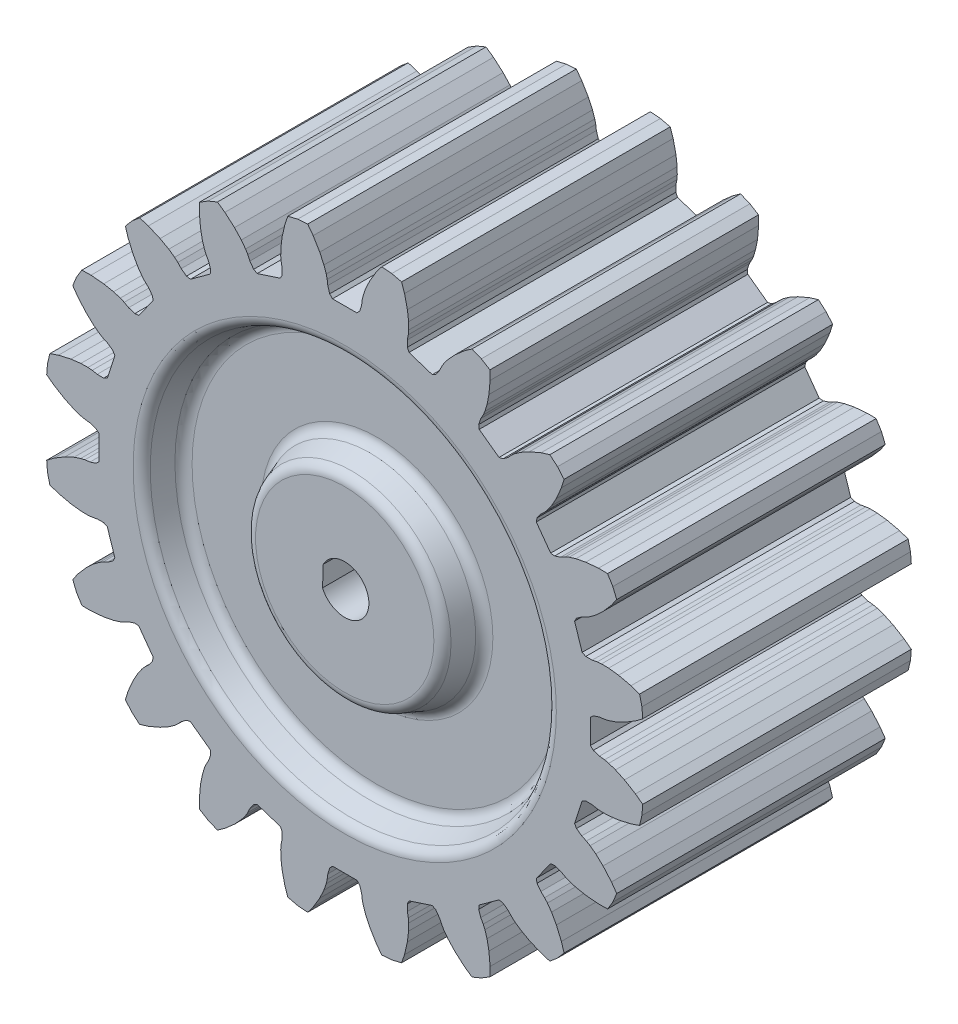
SolidWorks part; units mm, degrees
ref_plane "Plano frontal" through (0, 0, 0) normal (0, 0, 1) x (1, 0, 0)
ref_plane "Plano superior" through (0, 0, 0) normal (0, 1, 0) x (1, 0, 0)
ref_plane "Plano direito" through (0, 0, 0) normal (1, 0, 0) x (0, 0, -1)
sketch "Esboço1" plane through (0, 0, 0) normal (0, 0, 1) x (1, 0, 0)
  line L0 (-1.9823, 5.2954) -> (-2.2016, 4.3819)
  line L1 (-2.2016, 4.3819) -> (-2.2753, 3.4454)
  line L2 (-2.2753, 3.4454) -> (-1.5987, 2.9377)
  line L3 (-1.5987, 2.9377) -> (-0.5759, 2.326)
  line L4 (-0.5759, 2.326) -> (0.2653, 1.9359)
  line L5 (0.2653, 1.9359) -> (0.8924, 1.7214)
  line L6 (0.8924, 1.7214) -> (1.2807, 1.6326)
  line L7 (1.2807, 1.6326) -> (1.7506, 1.5759)
  line L8 (1.7506, 1.5759) -> (2.324, 1.394)
  line L9 (2.324, 1.394) -> (2.5965, 1.1386)
  line L10 (2.5965, 1.1386) -> (2.5965, -1.1386)
  line L11 (2.5965, -1.1386) -> (2.324, -1.394)
  line L12 (2.324, -1.394) -> (1.7506, -1.5759)
  line L13 (1.7506, -1.5759) -> (1.2807, -1.6326)
  line L14 (1.2807, -1.6326) -> (0.8924, -1.7214)
  line L15 (0.8924, -1.7214) -> (0.2653, -1.9359)
  line L16 (0.2653, -1.9359) -> (-0.5759, -2.326)
  line L17 (-0.5759, -2.326) -> (-1.5987, -2.9377)
  line L18 (-1.5987, -2.9377) -> (-2.2753, -3.4454)
  line L19 (-2.2753, -3.4454) -> (-2.2016, -4.3819)
  line L20 (-2.2016, -4.3819) -> (-1.9823, -5.2954)
  line L21 (-1.9823, -5.2954) -> (-1.1819, -5.5692)
  line L22 (-1.1819, -5.5692) -> (-0.0202, -5.8348)
  line L23 (-0.0202, -5.8348) -> (0.9004, -5.946)
  line L24 (0.9004, -5.946) -> (1.5631, -5.9562)
  line L25 (1.5631, -5.9562) -> (1.9598, -5.9206)
  line L26 (1.9598, -5.9206) -> (2.4243, -5.8293)
  line L27 (2.4243, -5.8293) -> (3.0258, -5.8251)
  line L28 (3.0258, -5.8251) -> (3.3639, -5.9839)
  line L29 (3.3639, -5.9839) -> (4.0676, -8.1495)
  line L30 (4.0676, -8.1495) -> (3.8874, -8.4767)
  line L31 (3.8874, -8.4767) -> (3.3983, -8.8268)
  line L32 (3.3983, -8.8268) -> (2.9688, -9.026)
  line L33 (2.9688, -9.026) -> (2.627, -9.2304)
  line L34 (2.627, -9.2304) -> (2.0968, -9.6282)
  line L35 (2.0968, -9.6282) -> (1.4174, -10.2592)
  line L36 (1.4174, -10.2592) -> (0.6337, -11.157)
  line L37 (0.6337, -11.157) -> (0.1471, -11.8489)
  line L38 (0.1471, -11.8489) -> (0.5066, -12.7169)
  line L39 (0.5066, -12.7169) -> (0.9974, -13.5179)
  line L40 (0.9974, -13.5179) -> (1.8433, -13.5309)
  line L41 (1.8433, -13.5309) -> (3.0302, -13.4246)
  line L42 (3.0302, -13.4246) -> (3.9401, -13.2457)
  line L43 (3.9401, -13.2457) -> (4.5735, -13.0507)
  line L44 (4.5735, -13.0507) -> (4.9398, -12.8943)
  line L45 (4.9398, -12.8943) -> (5.3534, -12.6639)
  line L46 (5.3534, -12.6639) -> (5.9241, -12.4741)
  line L47 (5.9241, -12.4741) -> (6.2947, -12.5205)
  line L48 (6.2947, -12.5205) -> (7.6332, -14.3628)
  line L49 (7.6332, -14.3628) -> (7.5629, -14.7296)
  line L50 (7.5629, -14.7296) -> (7.2059, -15.2137)
  line L51 (7.2059, -15.2137) -> (6.859, -15.5359)
  line L52 (6.859, -15.5359) -> (6.5971, -15.8359)
  line L53 (6.5971, -15.8359) -> (6.2158, -16.3781)
  line L54 (6.2158, -16.3781) -> (5.7646, -17.1881)
  line L55 (5.7646, -17.1881) -> (5.2967, -18.2841)
  line L56 (5.2967, -18.2841) -> (5.0477, -19.0926)
  line L57 (5.0477, -19.0926) -> (5.6578, -19.807)
  line L58 (5.6578, -19.807) -> (6.3722, -20.4171)
  line L59 (6.3722, -20.4171) -> (7.1807, -20.1681)
  line L60 (7.1807, -20.1681) -> (8.2767, -19.7002)
  line L61 (8.2767, -19.7002) -> (9.0867, -19.249)
  line L62 (9.0867, -19.249) -> (9.6289, -18.8677)
  line L63 (9.6289, -18.8677) -> (9.9289, -18.6058)
  line L64 (9.9289, -18.6058) -> (10.251, -18.2589)
  line L65 (10.251, -18.2589) -> (10.7352, -17.9019)
  line L66 (10.7352, -17.9019) -> (11.102, -17.8316)
  line L67 (11.102, -17.8316) -> (12.9442, -19.1701)
  line L68 (12.9442, -19.1701) -> (12.9907, -19.5407)
  line L69 (12.9907, -19.5407) -> (12.8009, -20.1114)
  line L70 (12.8009, -20.1114) -> (12.5705, -20.525)
  line L71 (12.5705, -20.525) -> (12.4141, -20.8913)
  line L72 (12.4141, -20.8913) -> (12.219, -21.5247)
  line L73 (12.219, -21.5247) -> (12.0402, -22.4346)
  line L74 (12.0402, -22.4346) -> (11.9339, -23.6215)
  line L75 (11.9339, -23.6215) -> (11.9469, -24.4674)
  line L76 (11.9469, -24.4674) -> (12.7479, -24.9582)
  line L77 (12.7479, -24.9582) -> (13.6159, -25.3177)
  line L78 (13.6159, -25.3177) -> (14.3078, -24.8311)
  line L79 (14.3078, -24.8311) -> (15.2056, -24.0474)
  line L80 (15.2056, -24.0474) -> (15.8366, -23.3679)
  line L81 (15.8366, -23.3679) -> (16.2344, -22.8378)
  line L82 (16.2344, -22.8378) -> (16.4388, -22.496)
  line L83 (16.4388, -22.496) -> (16.638, -22.0665)
  line L84 (16.638, -22.0665) -> (16.9881, -21.5774)
  line L85 (16.9881, -21.5774) -> (17.3153, -21.3972)
  line L86 (17.3153, -21.3972) -> (19.4809, -22.1009)
  line L87 (19.4809, -22.1009) -> (19.6397, -22.439)
  line L88 (19.6397, -22.439) -> (19.6355, -23.0405)
  line L89 (19.6355, -23.0405) -> (19.5442, -23.505)
  line L90 (19.5442, -23.505) -> (19.5086, -23.9017)
  line L91 (19.5086, -23.9017) -> (19.5188, -24.5644)
  line L92 (19.5188, -24.5644) -> (19.6299, -25.4849)
  line L93 (19.6299, -25.4849) -> (19.8956, -26.6467)
  line L94 (19.8956, -26.6467) -> (20.1694, -27.4471)
  line L95 (20.1694, -27.4471) -> (21.0829, -27.6664)
  line L96 (21.0829, -27.6664) -> (22.0194, -27.7401)
  line L97 (22.0194, -27.7401) -> (22.5271, -27.0635)
  line L98 (22.5271, -27.0635) -> (23.1388, -26.0407)
  line L99 (23.1388, -26.0407) -> (23.5289, -25.1995)
  line L100 (23.5289, -25.1995) -> (23.7434, -24.5724)
  line L101 (23.7434, -24.5724) -> (23.8322, -24.1841)
  line L102 (23.8322, -24.1841) -> (23.8889, -23.7142)
  line L103 (23.8889, -23.7142) -> (24.0708, -23.1408)
  line L104 (24.0708, -23.1408) -> (24.3262, -22.8683)
  line L105 (24.3262, -22.8683) -> (26.6033, -22.8683)
  line L106 (26.6033, -22.8683) -> (26.8588, -23.1408)
  line L107 (26.8588, -23.1408) -> (27.0407, -23.7142)
  line L108 (27.0407, -23.7142) -> (27.0974, -24.1841)
  line L109 (27.0974, -24.1841) -> (27.1862, -24.5724)
  line L110 (27.1862, -24.5724) -> (27.4007, -25.1995)
  line L111 (27.4007, -25.1995) -> (27.7908, -26.0407)
  line L112 (27.7908, -26.0407) -> (28.4025, -27.0635)
  line L113 (28.4025, -27.0635) -> (28.9102, -27.7401)
  line L114 (28.9102, -27.7401) -> (29.8467, -27.6664)
  line L115 (29.8467, -27.6664) -> (30.7602, -27.4471)
  line L116 (30.7602, -27.4471) -> (31.034, -26.6467)
  line L117 (31.034, -26.6467) -> (31.2996, -25.4849)
  line L118 (31.2996, -25.4849) -> (31.4107, -24.5644)
  line L119 (31.4107, -24.5644) -> (31.4209, -23.9017)
  line L120 (31.4209, -23.9017) -> (31.3854, -23.505)
  line L121 (31.3854, -23.505) -> (31.2941, -23.0405)
  line L122 (31.2941, -23.0405) -> (31.2899, -22.439)
  line L123 (31.2899, -22.439) -> (31.4487, -22.1009)
  line L124 (31.4487, -22.1009) -> (33.6143, -21.3972)
  line L125 (33.6143, -21.3972) -> (33.9414, -21.5774)
  line L126 (33.9414, -21.5774) -> (34.2916, -22.0665)
  line L127 (34.2916, -22.0665) -> (34.4908, -22.496)
  line L128 (34.4908, -22.496) -> (34.6952, -22.8378)
  line L129 (34.6952, -22.8378) -> (35.093, -23.3679)
  line L130 (35.093, -23.3679) -> (35.724, -24.0474)
  line L131 (35.724, -24.0474) -> (36.6218, -24.8311)
  line L132 (36.6218, -24.8311) -> (37.3137, -25.3177)
  line L133 (37.3137, -25.3177) -> (38.1816, -24.9582)
  line L134 (38.1816, -24.9582) -> (38.9826, -24.4674)
  line L135 (38.9826, -24.4674) -> (38.9957, -23.6215)
  line L136 (38.9957, -23.6215) -> (38.8893, -22.4346)
  line L137 (38.8893, -22.4346) -> (38.7105, -21.5247)
  line L138 (38.7105, -21.5247) -> (38.5155, -20.8913)
  line L139 (38.5155, -20.8913) -> (38.3591, -20.525)
  line L140 (38.3591, -20.525) -> (38.1287, -20.1114)
  line L141 (38.1287, -20.1114) -> (37.9388, -19.5407)
  line L142 (37.9388, -19.5407) -> (37.9853, -19.1701)
  line L143 (37.9853, -19.1701) -> (39.8276, -17.8316)
  line L144 (39.8276, -17.8316) -> (40.1944, -17.9019)
  line L145 (40.1944, -17.9019) -> (40.6785, -18.2589)
  line L146 (40.6785, -18.2589) -> (41.0007, -18.6058)
  line L147 (41.0007, -18.6058) -> (41.3007, -18.8677)
  line L148 (41.3007, -18.8677) -> (41.8429, -19.249)
  line L149 (41.8429, -19.249) -> (42.6529, -19.7002)
  line L150 (42.6529, -19.7002) -> (43.7489, -20.1681)
  line L151 (43.7489, -20.1681) -> (44.5574, -20.4171)
  line L152 (44.5574, -20.4171) -> (45.2717, -19.807)
  line L153 (45.2717, -19.807) -> (45.8819, -19.0926)
  line L154 (45.8819, -19.0926) -> (45.6329, -18.2841)
  line L155 (45.6329, -18.2841) -> (45.165, -17.1881)
  line L156 (45.165, -17.1881) -> (44.7138, -16.3781)
  line L157 (44.7138, -16.3781) -> (44.3325, -15.8359)
  line L158 (44.3325, -15.8359) -> (44.0705, -15.5359)
  line L159 (44.0705, -15.5359) -> (43.7237, -15.2137)
  line L160 (43.7237, -15.2137) -> (43.3667, -14.7296)
  line L161 (43.3667, -14.7296) -> (43.2964, -14.3628)
  line L162 (43.2964, -14.3628) -> (44.6349, -12.5205)
  line L163 (44.6349, -12.5205) -> (45.0054, -12.4741)
  line L164 (45.0054, -12.4741) -> (45.5762, -12.6639)
  line L165 (45.5762, -12.6639) -> (45.9898, -12.8943)
  line L166 (45.9898, -12.8943) -> (46.3561, -13.0507)
  line L167 (46.3561, -13.0507) -> (46.9895, -13.2457)
  line L168 (46.9895, -13.2457) -> (47.8993, -13.4246)
  line L169 (47.8993, -13.4246) -> (49.0863, -13.5309)
  line L170 (49.0863, -13.5309) -> (49.9322, -13.5179)
  line L171 (49.9322, -13.5179) -> (50.423, -12.7169)
  line L172 (50.423, -12.7169) -> (50.7825, -11.8489)
  line L173 (50.7825, -11.8489) -> (50.2959, -11.157)
  line L174 (50.2959, -11.157) -> (49.5122, -10.2592)
  line L175 (49.5122, -10.2592) -> (48.8327, -9.6282)
  line L176 (48.8327, -9.6282) -> (48.3026, -9.2304)
  line L177 (48.3026, -9.2304) -> (47.9608, -9.026)
  line L178 (47.9608, -9.026) -> (47.5313, -8.8268)
  line L179 (47.5313, -8.8268) -> (47.0422, -8.4767)
  line L180 (47.0422, -8.4767) -> (46.862, -8.1495)
  line L181 (46.862, -8.1495) -> (47.5657, -5.9839)
  line L182 (47.5657, -5.9839) -> (47.9038, -5.8251)
  line L183 (47.9038, -5.8251) -> (48.5053, -5.8293)
  line L184 (48.5053, -5.8293) -> (48.9698, -5.9206)
  line L185 (48.9698, -5.9206) -> (49.3665, -5.9562)
  line L186 (49.3665, -5.9562) -> (50.0292, -5.946)
  line L187 (50.0292, -5.946) -> (50.9497, -5.8348)
  line L188 (50.9497, -5.8348) -> (52.1115, -5.5692)
  line L189 (52.1115, -5.5692) -> (52.9119, -5.2954)
  line L190 (52.9119, -5.2954) -> (53.1312, -4.3819)
  line L191 (53.1312, -4.3819) -> (53.2049, -3.4454)
  line L192 (53.2049, -3.4454) -> (52.5282, -2.9377)
  line L193 (52.5282, -2.9377) -> (51.5055, -2.326)
  line L194 (51.5055, -2.326) -> (50.6643, -1.9359)
  line L195 (50.6643, -1.9359) -> (50.0372, -1.7214)
  line L196 (50.0372, -1.7214) -> (49.6489, -1.6326)
  line L197 (49.6489, -1.6326) -> (49.179, -1.5759)
  line L198 (49.179, -1.5759) -> (48.6056, -1.394)
  line L199 (48.6056, -1.394) -> (48.3331, -1.1386)
  line L200 (48.3331, -1.1386) -> (48.3331, 1.1386)
  line L201 (48.3331, 1.1386) -> (48.6056, 1.394)
  line L202 (48.6056, 1.394) -> (49.179, 1.5759)
  line L203 (49.179, 1.5759) -> (49.6489, 1.6326)
  line L204 (49.6489, 1.6326) -> (50.0372, 1.7214)
  line L205 (50.0372, 1.7214) -> (50.6643, 1.9359)
  line L206 (50.6643, 1.9359) -> (51.5055, 2.326)
  line L207 (51.5055, 2.326) -> (52.5282, 2.9377)
  line L208 (52.5282, 2.9377) -> (53.2049, 3.4454)
  line L209 (53.2049, 3.4454) -> (53.1312, 4.3819)
  line L210 (53.1312, 4.3819) -> (52.9119, 5.2954)
  line L211 (52.9119, 5.2954) -> (52.1115, 5.5692)
  line L212 (52.1115, 5.5692) -> (50.9497, 5.8348)
  line L213 (50.9497, 5.8348) -> (50.0292, 5.946)
  line L214 (50.0292, 5.946) -> (49.3665, 5.9562)
  line L215 (49.3665, 5.9562) -> (48.9698, 5.9206)
  line L216 (48.9698, 5.9206) -> (48.5053, 5.8293)
  line L217 (48.5053, 5.8293) -> (47.9038, 5.8251)
  line L218 (47.9038, 5.8251) -> (47.5657, 5.9839)
  line L219 (47.5657, 5.9839) -> (46.862, 8.1495)
  line L220 (46.862, 8.1495) -> (47.0422, 8.4767)
  line L221 (47.0422, 8.4767) -> (47.5313, 8.8268)
  line L222 (47.5313, 8.8268) -> (47.9608, 9.026)
  line L223 (47.9608, 9.026) -> (48.3026, 9.2304)
  line L224 (48.3026, 9.2304) -> (48.8327, 9.6282)
  line L225 (48.8327, 9.6282) -> (49.5122, 10.2592)
  line L226 (49.5122, 10.2592) -> (50.2959, 11.157)
  line L227 (50.2959, 11.157) -> (50.7825, 11.8489)
  line L228 (50.7825, 11.8489) -> (50.423, 12.7169)
  line L229 (50.423, 12.7169) -> (49.9322, 13.5179)
  line L230 (49.9322, 13.5179) -> (49.0863, 13.5309)
  line L231 (49.0863, 13.5309) -> (47.8993, 13.4246)
  line L232 (47.8993, 13.4246) -> (46.9895, 13.2457)
  line L233 (46.9895, 13.2457) -> (46.3561, 13.0507)
  line L234 (46.3561, 13.0507) -> (45.9898, 12.8943)
  line L235 (45.9898, 12.8943) -> (45.5762, 12.6639)
  line L236 (45.5762, 12.6639) -> (45.0054, 12.4741)
  line L237 (45.0054, 12.4741) -> (44.6349, 12.5205)
  line L238 (44.6349, 12.5205) -> (43.2964, 14.3628)
  line L239 (43.2964, 14.3628) -> (43.3667, 14.7296)
  line L240 (43.3667, 14.7296) -> (43.7237, 15.2137)
  line L241 (43.7237, 15.2137) -> (44.0705, 15.5359)
  line L242 (44.0705, 15.5359) -> (44.3325, 15.8359)
  line L243 (44.3325, 15.8359) -> (44.7138, 16.3781)
  line L244 (44.7138, 16.3781) -> (45.165, 17.1881)
  line L245 (45.165, 17.1881) -> (45.6329, 18.2841)
  line L246 (45.6329, 18.2841) -> (45.8819, 19.0926)
  line L247 (45.8819, 19.0926) -> (45.2717, 19.807)
  line L248 (45.2717, 19.807) -> (44.5574, 20.4171)
  line L249 (44.5574, 20.4171) -> (43.7489, 20.1681)
  line L250 (43.7489, 20.1681) -> (42.6529, 19.7002)
  line L251 (42.6529, 19.7002) -> (41.8429, 19.249)
  line L252 (41.8429, 19.249) -> (41.3007, 18.8677)
  line L253 (41.3007, 18.8677) -> (41.0007, 18.6058)
  line L254 (41.0007, 18.6058) -> (40.6785, 18.2589)
  line L255 (40.6785, 18.2589) -> (40.1944, 17.9019)
  line L256 (40.1944, 17.9019) -> (39.8276, 17.8316)
  line L257 (39.8276, 17.8316) -> (37.9853, 19.1701)
  line L258 (37.9853, 19.1701) -> (37.9388, 19.5407)
  line L259 (37.9388, 19.5407) -> (38.1287, 20.1114)
  line L260 (38.1287, 20.1114) -> (38.3591, 20.525)
  line L261 (38.3591, 20.525) -> (38.5155, 20.8913)
  line L262 (38.5155, 20.8913) -> (38.7105, 21.5247)
  line L263 (38.7105, 21.5247) -> (38.8893, 22.4346)
  line L264 (38.8893, 22.4346) -> (38.9957, 23.6215)
  line L265 (38.9957, 23.6215) -> (38.9826, 24.4674)
  line L266 (38.9826, 24.4674) -> (38.1816, 24.9582)
  line L267 (38.1816, 24.9582) -> (37.3137, 25.3177)
  line L268 (37.3137, 25.3177) -> (36.6218, 24.8311)
  line L269 (36.6218, 24.8311) -> (35.724, 24.0474)
  line L270 (35.724, 24.0474) -> (35.093, 23.3679)
  line L271 (35.093, 23.3679) -> (34.6952, 22.8378)
  line L272 (34.6952, 22.8378) -> (34.4908, 22.496)
  line L273 (34.4908, 22.496) -> (34.2916, 22.0665)
  line L274 (34.2916, 22.0665) -> (33.9414, 21.5774)
  line L275 (33.9414, 21.5774) -> (33.6143, 21.3972)
  line L276 (33.6143, 21.3972) -> (31.4487, 22.1009)
  line L277 (31.4487, 22.1009) -> (31.2899, 22.439)
  line L278 (31.2899, 22.439) -> (31.2941, 23.0405)
  line L279 (31.2941, 23.0405) -> (31.3854, 23.505)
  line L280 (31.3854, 23.505) -> (31.4209, 23.9017)
  line L281 (31.4209, 23.9017) -> (31.4107, 24.5644)
  line L282 (31.4107, 24.5644) -> (31.2996, 25.4849)
  line L283 (31.2996, 25.4849) -> (31.034, 26.6467)
  line L284 (31.034, 26.6467) -> (30.7602, 27.4471)
  line L285 (30.7602, 27.4471) -> (29.8467, 27.6664)
  line L286 (29.8467, 27.6664) -> (28.9102, 27.7401)
  line L287 (28.9102, 27.7401) -> (28.4025, 27.0635)
  line L288 (28.4025, 27.0635) -> (27.7908, 26.0407)
  line L289 (27.7908, 26.0407) -> (27.4007, 25.1995)
  line L290 (27.4007, 25.1995) -> (27.1862, 24.5724)
  line L291 (27.1862, 24.5724) -> (27.0974, 24.1841)
  line L292 (27.0974, 24.1841) -> (27.0407, 23.7142)
  line L293 (27.0407, 23.7142) -> (26.8588, 23.1408)
  line L294 (26.8588, 23.1408) -> (26.6033, 22.8683)
  line L295 (26.6033, 22.8683) -> (24.3262, 22.8683)
  line L296 (24.3262, 22.8683) -> (24.0708, 23.1408)
  line L297 (24.0708, 23.1408) -> (23.8889, 23.7142)
  line L298 (23.8889, 23.7142) -> (23.8322, 24.1841)
  line L299 (23.8322, 24.1841) -> (23.7434, 24.5724)
  line L300 (23.7434, 24.5724) -> (23.5289, 25.1995)
  line L301 (23.5289, 25.1995) -> (23.1388, 26.0407)
  line L302 (23.1388, 26.0407) -> (22.5271, 27.0635)
  line L303 (22.5271, 27.0635) -> (22.0194, 27.7401)
  line L304 (22.0194, 27.7401) -> (21.0829, 27.6664)
  line L305 (21.0829, 27.6664) -> (20.1694, 27.4471)
  line L306 (20.1694, 27.4471) -> (19.8956, 26.6467)
  line L307 (19.8956, 26.6467) -> (19.6299, 25.4849)
  line L308 (19.6299, 25.4849) -> (19.5188, 24.5644)
  line L309 (19.5188, 24.5644) -> (19.5086, 23.9017)
  line L310 (19.5086, 23.9017) -> (19.5442, 23.505)
  line L311 (19.5442, 23.505) -> (19.6355, 23.0405)
  line L312 (19.6355, 23.0405) -> (19.6397, 22.439)
  line L313 (19.6397, 22.439) -> (19.4809, 22.1009)
  line L314 (19.4809, 22.1009) -> (17.3153, 21.3972)
  line L315 (17.3153, 21.3972) -> (16.9881, 21.5774)
  line L316 (16.9881, 21.5774) -> (16.638, 22.0665)
  line L317 (16.638, 22.0665) -> (16.4388, 22.496)
  line L318 (16.4388, 22.496) -> (16.2344, 22.8378)
  line L319 (16.2344, 22.8378) -> (15.8366, 23.3679)
  line L320 (15.8366, 23.3679) -> (15.2056, 24.0474)
  line L321 (15.2056, 24.0474) -> (14.3078, 24.8311)
  line L322 (14.3078, 24.8311) -> (13.6159, 25.3177)
  line L323 (13.6159, 25.3177) -> (12.7479, 24.9582)
  line L324 (12.7479, 24.9582) -> (11.9469, 24.4674)
  line L325 (11.9469, 24.4674) -> (11.9339, 23.6215)
  line L326 (11.9339, 23.6215) -> (12.0402, 22.4346)
  line L327 (12.0402, 22.4346) -> (12.219, 21.5247)
  line L328 (12.219, 21.5247) -> (12.4141, 20.8913)
  line L329 (12.4141, 20.8913) -> (12.5705, 20.525)
  line L330 (12.5705, 20.525) -> (12.8009, 20.1114)
  line L331 (12.8009, 20.1114) -> (12.9907, 19.5407)
  line L332 (12.9907, 19.5407) -> (12.9442, 19.1701)
  line L333 (12.9442, 19.1701) -> (11.102, 17.8316)
  line L334 (11.102, 17.8316) -> (10.7352, 17.9019)
  line L335 (10.7352, 17.9019) -> (10.251, 18.2589)
  line L336 (10.251, 18.2589) -> (9.9289, 18.6058)
  line L337 (9.9289, 18.6058) -> (9.6289, 18.8677)
  line L338 (9.6289, 18.8677) -> (9.0867, 19.249)
  line L339 (9.0867, 19.249) -> (8.2767, 19.7002)
  line L340 (8.2767, 19.7002) -> (7.1807, 20.1681)
  line L341 (7.1807, 20.1681) -> (6.3722, 20.4171)
  line L342 (6.3722, 20.4171) -> (5.6578, 19.807)
  line L343 (5.6578, 19.807) -> (5.0477, 19.0926)
  line L344 (5.0477, 19.0926) -> (5.2967, 18.2841)
  line L345 (5.2967, 18.2841) -> (5.7646, 17.1881)
  line L346 (5.7646, 17.1881) -> (6.2158, 16.3781)
  line L347 (6.2158, 16.3781) -> (6.5971, 15.8359)
  line L348 (6.5971, 15.8359) -> (6.859, 15.5359)
  line L349 (6.859, 15.5359) -> (7.2059, 15.2137)
  line L350 (7.2059, 15.2137) -> (7.5629, 14.7296)
  line L351 (7.5629, 14.7296) -> (7.6332, 14.3628)
  line L352 (7.6332, 14.3628) -> (6.2947, 12.5205)
  line L353 (6.2947, 12.5205) -> (5.9241, 12.4741)
  line L354 (5.9241, 12.4741) -> (5.3534, 12.6639)
  line L355 (5.3534, 12.6639) -> (4.9398, 12.8943)
  line L356 (4.9398, 12.8943) -> (4.5735, 13.0507)
  line L357 (4.5735, 13.0507) -> (3.9401, 13.2457)
  line L358 (3.9401, 13.2457) -> (3.0302, 13.4246)
  line L359 (3.0302, 13.4246) -> (1.8433, 13.5309)
  line L360 (1.8433, 13.5309) -> (0.9974, 13.5179)
  line L361 (0.9974, 13.5179) -> (0.5066, 12.7169)
  line L362 (0.5066, 12.7169) -> (0.1471, 11.8489)
  line L363 (0.1471, 11.8489) -> (0.6337, 11.157)
  line L364 (0.6337, 11.157) -> (1.4174, 10.2592)
  line L365 (1.4174, 10.2592) -> (2.0968, 9.6282)
  line L366 (2.0968, 9.6282) -> (2.627, 9.2304)
  line L367 (2.627, 9.2304) -> (2.9688, 9.026)
  line L368 (2.9688, 9.026) -> (3.3983, 8.8268)
  line L369 (3.3983, 8.8268) -> (3.8874, 8.4767)
  line L370 (3.8874, 8.4767) -> (4.0676, 8.1495)
  line L371 (4.0676, 8.1495) -> (3.3639, 5.9839)
  line L372 (3.3639, 5.9839) -> (3.0258, 5.8251)
  line L373 (3.0258, 5.8251) -> (2.4243, 5.8293)
  line L374 (2.4243, 5.8293) -> (1.9598, 5.9206)
  line L375 (1.9598, 5.9206) -> (1.5631, 5.9562)
  line L376 (1.5631, 5.9562) -> (0.9004, 5.946)
  line L377 (0.9004, 5.946) -> (-0.0202, 5.8348)
  line L378 (-0.0202, 5.8348) -> (-1.1819, 5.5692)
  line L379 (-1.1819, 5.5692) -> (-1.9823, 5.2954)
  circle A0 centre (25.4648, 0) radius 5
  dimension "D1" = 10
extrude "Ressalto-extrusão1" add sketch "Esboço1" along normal mid plane 25
sketch "Esboço2" plane through (0, 0, 12.5) normal (0, 0, 1) x (1, 0, 0)
  circle A0 centre (25.4648, 0) radius 19
  circle A1 centre (25.4648, 0) radius 9
  dimension "D1" = 18
  dimension "D2" = 38
extrude "Corte-extrusão1" cut sketch "Esboço2" against normal blind 3 draft 20
mirror "Espelhar1" about plane through (0, 0, 0) normal (0, 0, 1) of "Corte-extrusão1"
fillet "Filete1" radius 1 8 edges at (35.5567, 0, 9.5) (34.4648, 0, 12.5) (43.3729, 0, 9.5) (44.4648, 0, 12.5) (15.3729, 0, -9.5) (34.4648, 0, -12.5) (44.4648, 0, -12.5) (7.5567, 0, -9.5)
sketch "Esboço3" plane through (0, 0, 0) normal (0, 0, 1) x (1, 0, 0)
  line L0 (23.9709, 0) -> (26.9587, 0)
  line L2 (23.9709, 0) -> (23.9709, 6.5)
  line L3 (23.9709, 6.5) -> (26.9587, 6.5)
  line L4 (26.9587, 0) -> (26.9587, 6.5)
  line L5 (25.4648, 0) -> (26.9587, 6.5) construction
  line L6 (23.9709, 6.5) -> (25.4648, 0) construction
  point P0 (25.4648, 0)
extrude "Corte-extrusão2" cut sketch "Esboço3" against normal mid plane 23
sketch "Sketch1" plane through (0, 0, -12.5) normal (0, 0, -1) x (-1, 0, 0)
  line L0 (-23.4017, -0.8979) -> (-23.4661, 1.0333)
  arc A0 (-23.4661, 1.0333) -> (-23.4017, -0.8979) centre (-25.4648, 0) ccw
  circle A1 centre (-25.4648, 0) radius 10.7921 construction
  circle A2 centre (-25.4648, 0) radius 6.0063
  dimension "D1" = 0
extrude "Boss-Extrude1" add sketch "Sketch1" against normal blind 25
